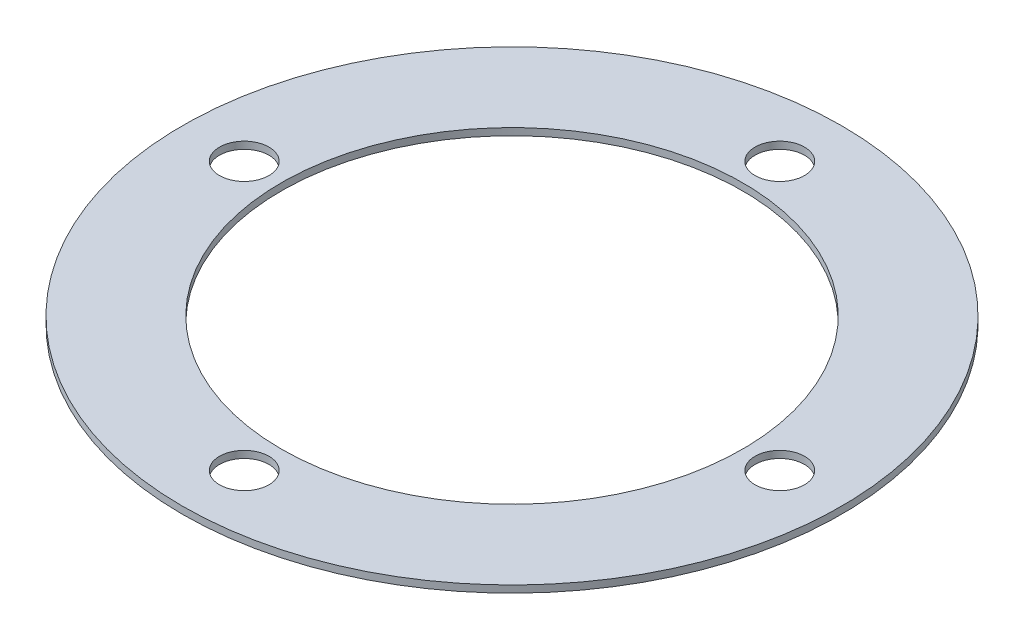
SolidWorks part; units mm, degrees
ref_plane "Front Plane" through (0, 0, 0) normal (0, 0, 1) x (1, 0, 0)
ref_plane "Top Plane" through (0, 0, 0) normal (0, 1, 0) x (1, 0, 0)
ref_plane "Right Plane" through (0, 0, 0) normal (1, 0, 0) x (0, 0, -1)
sketch "Sketch1" plane through (0, 0, 0) normal (0, 1, 0) x (1, 0, 0)
  line L9 (-40, 0) -> (0, 0) construction
  line L17 (0, 32.5) -> (0, 0) construction
  line L18 (0, 0) -> (32.5, 0) construction
  line L20 (0, -32.5) -> (0, 0) construction
  circle A0 centre (0, 0) radius 28
  circle A1 centre (0, 0) radius 32.5 construction
  circle A2 centre (0, 32.5) radius 3
  circle A3 centre (-32.5, 0) radius 3
  circle A4 centre (0, -32.5) radius 3
  circle A5 centre (32.5, 0) radius 3
  circle A11 centre (0, 0) radius 40
  point P3 (-40, 0)
  point P4 (-32.5, 0)
  dimension "D1" = 56
  dimension "D2" = 65
  dimension "D5" = 6
  dimension "D3" = 80
extrude "Boss-Extrude1" add sketch "Sketch1" along normal blind 0.86
